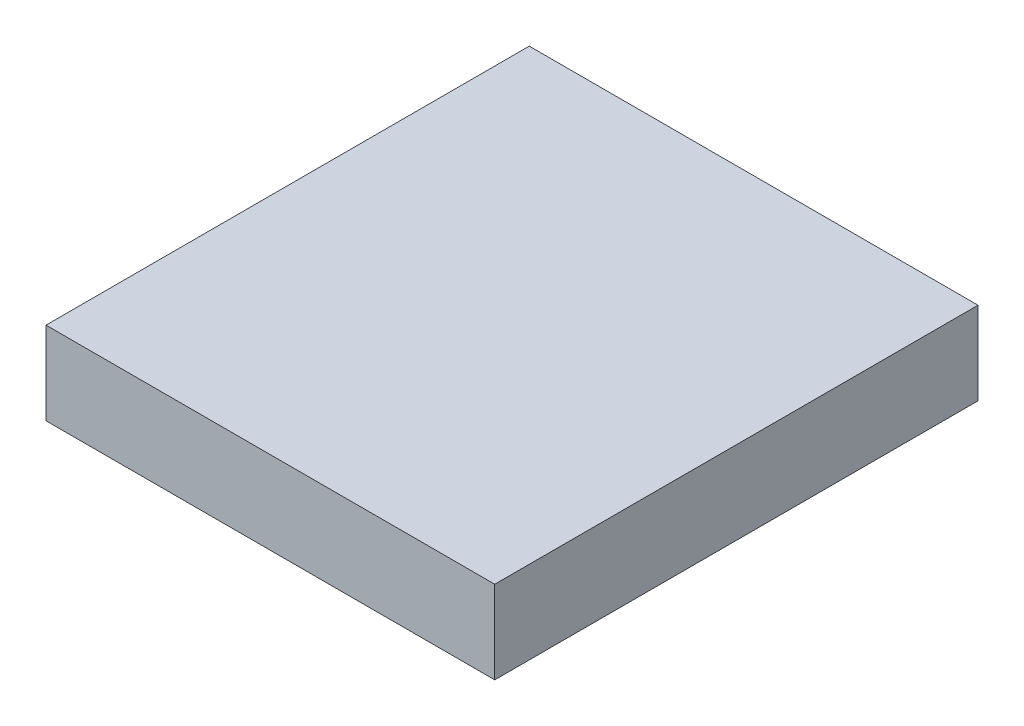
SolidWorks part; units mm, degrees
ref_plane "Front" through (0, 0, 0) normal (0, 0, 1) x (1, 0, 0)
ref_plane "Top" through (0, 0, 0) normal (0, 1, 0) x (1, 0, 0)
ref_plane "Right" through (0, 0, 0) normal (1, 0, 0) x (0, 0, -1)
sketch "Esquisse1" plane through (0, 0, 0) normal (0, 1, 0) x (1, 0, 0)
  line L1 (0, 0) -> (650, 0)
  line L2 (0, 0) -> (0, 700)
  line L3 (0, 700) -> (650, 700)
  line L4 (650, 0) -> (650, 700)
  dimension "D1" = 700
  dimension "D2" = 650
extrude "Boss.-Extru.1" add sketch "Esquisse1" along normal blind 120
